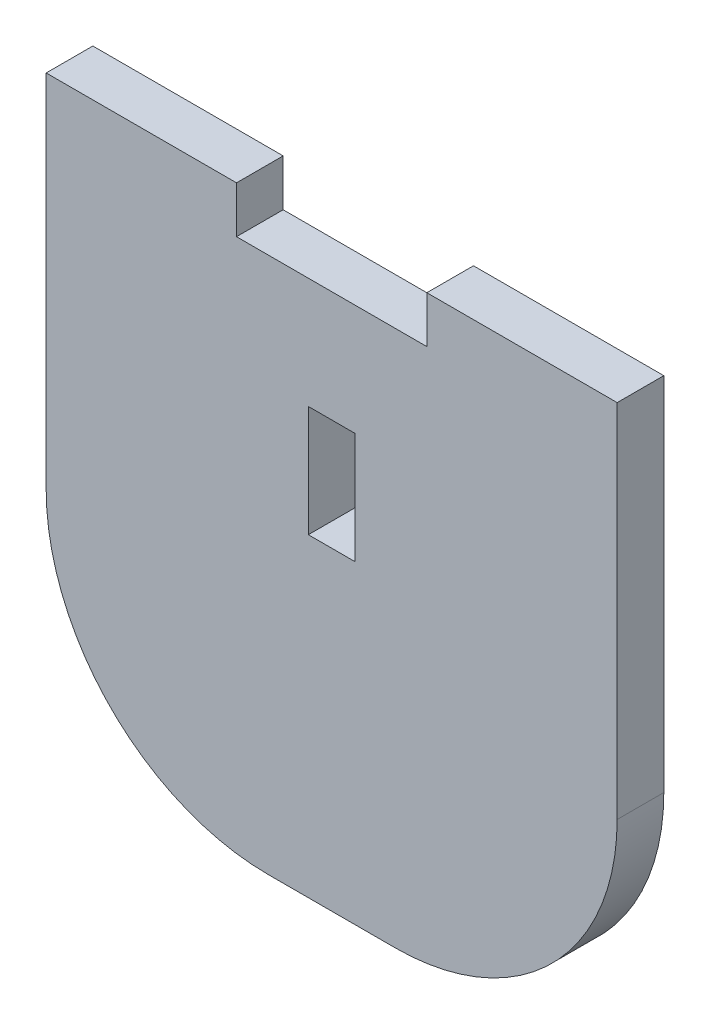
SolidWorks part; units mm, degrees
ref_plane "Front Plane" through (0, 0, 0) normal (0, 0, 1) x (1, 0, 0)
ref_plane "Top Plane" through (0, 0, 0) normal (0, 1, 0) x (1, 0, 0)
ref_plane "Right Plane" through (0, 0, 0) normal (1, 0, 0) x (0, 0, -1)
sketch "Sketch1" plane through (0, 0, 0) normal (0, 0, 1) x (1, 0, 0)
  line L1 (-95.7751, 117.3825) -> (-30.4971, 117.3825)
  line L2 (-95.7751, 117.3825) -> (-95.7751, 50.7075)
  line L3 (-95.7751, 50.7075) -> (-30.4971, 50.7075)
  line L4 (-30.4971, 117.3825) -> (-30.4971, 50.7075)
  dimension "D1" = 65.278
  dimension "D2" = 66.675
extrude "Boss-Extrude1" add sketch "Sketch1" along normal blind 5.334
sketch "Sketch2" plane through (0, 0, 5.334) normal (0, 0, 1) x (1, 0, 0)
  line L0 (-30.4971, 117.3825) -> (-95.7751, 117.3825) construction
  line L1 (-74.0158, 117.3825) -> (-52.2565, 117.3825)
  line L2 (-74.0158, 117.3825) -> (-74.0158, 112.0485)
  line L3 (-74.0158, 112.0485) -> (-52.2565, 112.0485)
  line L4 (-52.2565, 117.3825) -> (-52.2565, 112.0485)
  line L5 (-52.2565, 112.0485) -> (-30.4971, 112.0485) construction
  line L6 (-30.4971, 50.7075) -> (-30.4971, 117.3825) construction
  line L7 (-74.0158, 112.0485) -> (-95.7751, 112.0485) construction
  line L8 (-95.7751, 117.3825) -> (-95.7751, 50.7075) construction
  dimension "D1" = 5.334
extrude "Cut-Extrude1" cut sketch "Sketch2" against normal through all
fillet "Fillet1" radius 25.4 1 edges at (-95.7751, 50.7075, 2.667)
fillet "Fillet2" radius 25.4 1 edges at (-30.4971, 50.7075, 2.667)
sketch "Sketch3" plane through (0, 0, 5.334) normal (0, 0, 1) x (1, 0, 0)
  line L0 (-74.0158, 112.0485) -> (-52.2565, 112.0485) construction
  line L1 (-65.8031, 99.3485) -> (-60.4691, 99.3485)
  line L2 (-65.8031, 99.3485) -> (-65.8031, 86.6485)
  line L3 (-65.8031, 86.6485) -> (-60.4691, 86.6485)
  line L4 (-60.4691, 99.3485) -> (-60.4691, 86.6485)
  line L5 (-65.8031, 86.6485) -> (-95.7751, 86.6485) construction
  line L6 (-95.7751, 117.3825) -> (-95.7751, 76.1075) construction
  line L7 (-60.4691, 86.6485) -> (-30.4971, 86.6485) construction
  line L8 (-30.4971, 76.1075) -> (-30.4971, 117.3825) construction
  point P4 (-63.1361, 112.0485)
  dimension "D1" = 12.7
  dimension "D2" = 5.334
  dimension "D5" = 12.7
extrude "Cut-Extrude2" cut sketch "Sketch3" against normal through all
equation "\"MDF\"= .21in"
equation "\"Foamcore\"= .13in"
equation "\"Gmaterial\"= \"MDF\""
equation "\"D1@Boss-Extrude1\"=\"MDF\""
equation "\"D1@Sketch2\"=\"MDF\""
equation "\"D2@Sketch3\"=\"MDF\""
